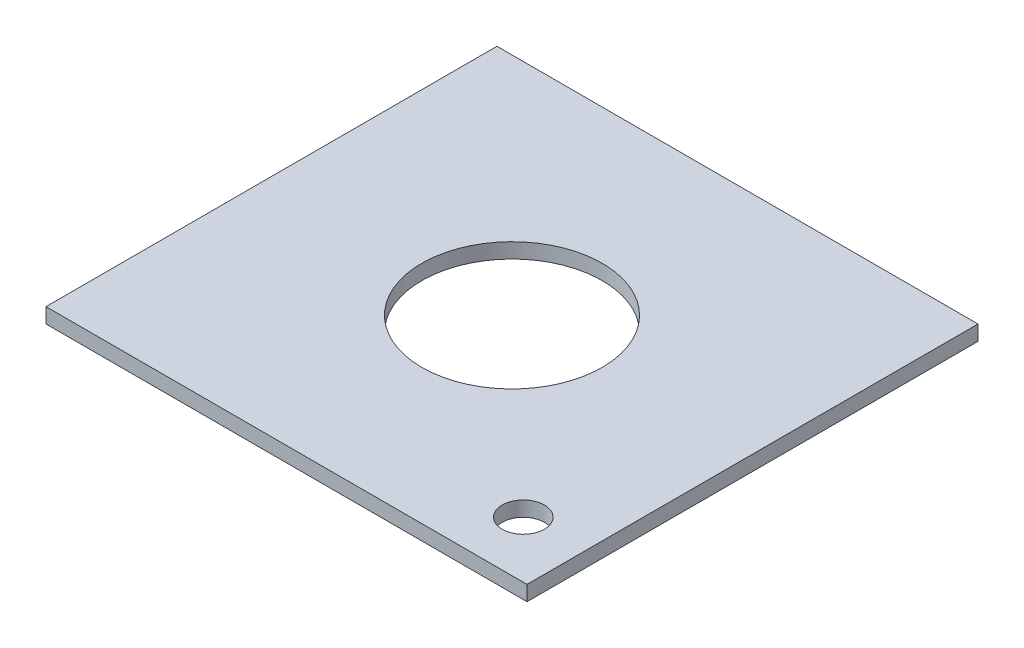
SolidWorks part; units mm, degrees
ref_plane "Front Plane" through (0, 0, 0) normal (0, 0, 1) x (1, 0, 0)
ref_plane "Top Plane" through (0, 0, 0) normal (0, 1, 0) x (1, 0, 0)
ref_plane "Right Plane" through (0, 0, 0) normal (1, 0, 0) x (0, 0, -1)
sketch "Sketch2" plane through (0, 0, 0) normal (0, 1, 0) x (1, 0, 0)
  line L1 (-40, 37.5) -> (40, 37.5)
  line L2 (-40, 37.5) -> (-40, -37.5)
  line L3 (-40, -37.5) -> (40, -37.5)
  line L4 (40, 37.5) -> (40, -37.5)
  line L5 (-40, 37.5) -> (40, -37.5) construction
  line L6 (-40, -37.5) -> (40, 37.5) construction
  circle A0 centre (0, 0) radius 15
  circle A1 centre (30, -28.125) radius 3.5
  point P0 (0, 0)
  dimension "D3" = 30
  dimension "D4" = 10
  dimension "D5" = 7
  dimension "D1" = 75
  dimension "D2" = 80
extrude "Boss-Extrude1" add sketch "Sketch2" along normal blind 2.5
